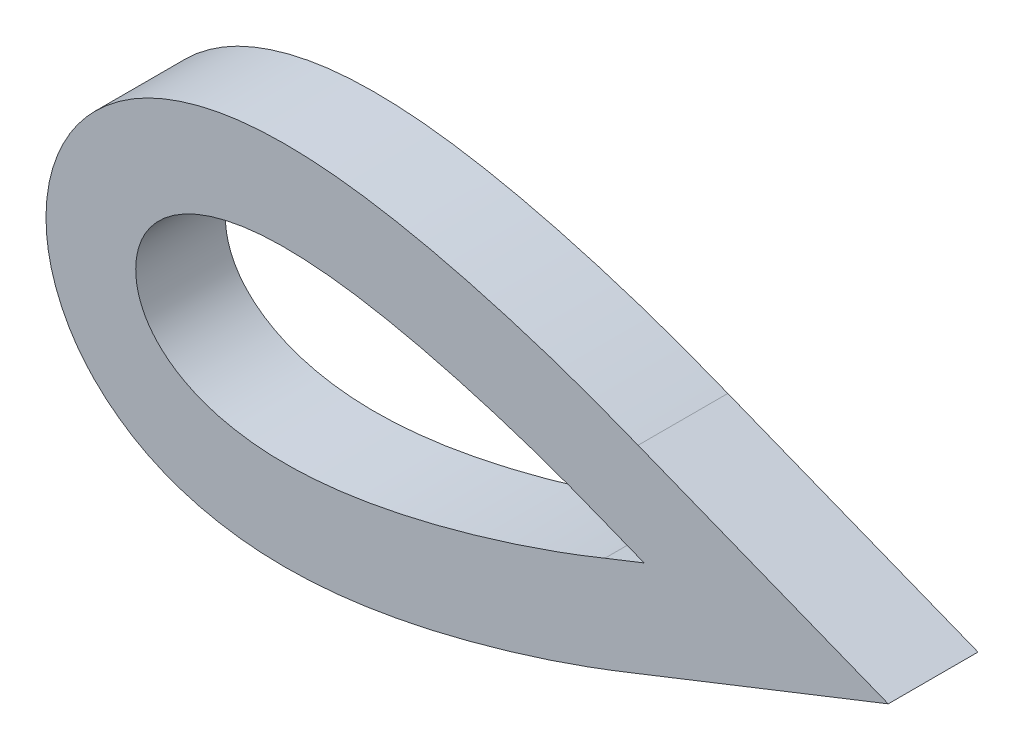
SolidWorks part; units mm, degrees
ref_plane "Front Plane" through (0, 0, 0) normal (0, 0, 1) x (1, 0, 0)
ref_plane "Top Plane" through (0, 0, 0) normal (0, 1, 0) x (1, 0, 0)
ref_plane "Right Plane" through (0, 0, 0) normal (1, 0, 0) x (0, 0, -1)
curve "Curve1"
  spline degree 3 poles (15, 0.0553, 0) (14.7504, 0.1555, 0) (14.2531, 0.3552, 0) (13.2557, 0.7272, 0) (12.0086, 1.1545, 0) (10.5081, 1.6108, 0) (9.0083, 2.0064, 0) (7.5085, 2.33, 0) (6.0074, 2.5603, 0) (4.7508, 2.6418, 0) (3.7477, 2.6098, 0) (2.9933, 2.5225, 0) (2.2339, 2.3534, 0) (1.6058, 2.116, 0) (1.1087, 1.8388, 0) (0.7182, 1.5477, 0) (0.3995, 1.204, 0) (0.0937, 0.6956, 0) (-0.0654, 0, 0) (0.0937, -0.6956, 0) (0.3995, -1.204, 0) (0.7182, -1.5477, 0) (1.1087, -1.8388, 0) (1.6058, -2.116, 0) (2.2339, -2.3534, 0) (2.9933, -2.5225, 0) (3.7477, -2.6098, 0) (4.7508, -2.6418, 0) (6.0074, -2.5603, 0) (7.5085, -2.33, 0) (9.0083, -2.0064, 0) (10.5081, -1.6108, 0) (12.0086, -1.1545, 0) (13.2557, -0.7272, 0) (14.2531, -0.3552, 0) (14.7504, -0.1555, 0) (15, -0.0553, 0) knots 0 0 0 0 0.024279 0.048376 0.096091 0.143261 0.189925 0.236074 0.281707 0.326919 0.349501 0.372229 0.39538 0.419578 0.432526 0.446653 0.463401 0.474441 0.5 0.525559 0.536599 0.553347 0.567474 0.580422 0.60462 0.627771 0.650499 0.673081 0.718293 0.763926 0.810075 0.856739 0.903909 0.951624 0.975721 1 1 1 1
sketch "Sketch2" plane through (0, 0, 0) normal (0, 0, 1) x (1, 0, 0)
  line L0 (-4.5404, 0) -> (25.6829, 0) construction
  line L1 (15.1863, -0.5193) -> (16.5, 0)
  line L2 (16.5, 0) -> (15.1863, 0.5193)
  line L3 (16.2965, -3.3063) -> (24.6607, 0)
  line L4 (24.6607, 0) -> (16.2965, 3.3063)
  spline S2 degree 1 poles (16.2965, 3.3063) (16.2965, -3.3063) knots 0 0 1 1 construction
  spline S3 degree 3 poles (-1320.7757, 4818.3054) (52.593, -66.6332) (43.0614, -10.0386) (13.8827, 1.0277) (13.5538, 1.1471) (12.5628, 1.4948) (11.897, 1.7114) (10.555, 2.113) (9.8788, 2.2983) (8.5131, 2.6287) (7.8237, 2.7742) (6.4262, 3.0035) (5.7175, 3.0874) (4.2802, 3.1439) (3.5498, 3.1187) (2.4551, 2.9201) (2.0895, 2.8263) (1.3734, 2.5578) (1.0227, 2.3846) (0.371, 1.9173) (0.0701, 1.622) (-0.2625, 1.0678) (-0.3513, 0.8634) (-0.4692, 0.441) (-0.5, 0.2215) (-0.5, -0.2215) (-0.4692, -0.441) (-0.3513, -0.8634) (-0.2625, -1.0678) (0.0701, -1.622) (0.371, -1.9173) (1.0227, -2.3846) (1.3734, -2.5578) (2.0895, -2.8263) (2.4551, -2.9201) (3.5498, -3.1187) (4.2802, -3.1439) (5.7175, -3.0874) (6.4262, -3.0035) (7.8237, -2.7742) (8.5131, -2.6287) (9.8788, -2.2983) (10.555, -2.113) (11.897, -1.7114) (12.5628, -1.4948) (13.5538, -1.1471) (13.8827, -1.0277) (43.0613, 10.0386) (52.5929, 66.6328) (-1320.7601, -4818.25) knots -2.715189 -2.715189 -2.715189 -2.715189 0.03125 0.03125 0.0625 0.0625 0.125 0.125 0.1875 0.1875 0.25 0.25 0.3125 0.3125 0.375 0.375 0.40625 0.40625 0.4375 0.4375 0.46875 0.46875 0.484375 0.484375 0.5 0.5 0.515625 0.515625 0.53125 0.53125 0.5625 0.5625 0.59375 0.59375 0.625 0.625 0.6875 0.6875 0.75 0.75 0.8125 0.8125 0.875 0.875 0.9375 0.9375 0.96875 0.96875 3.715178 3.715178 3.715178 3.715178 only from (15.1863, 0.5193) to (15.1863, -0.5193)
  spline S4 degree 3 poles (15.1863, 0.5193) (14.865, 0.6483) (14.5393, 0.7787) (13.8827, 1.0277) (13.5538, 1.1471) (12.5628, 1.4948) (11.897, 1.7114) (10.555, 2.113) (9.8788, 2.2983) (8.5131, 2.6287) (7.8237, 2.7742) (6.4262, 3.0035) (5.7175, 3.0874) (4.2802, 3.1439) (3.5498, 3.1187) (2.4551, 2.9201) (2.0895, 2.8263) (1.3734, 2.5578) (1.0227, 2.3846) (0.371, 1.9173) (0.0701, 1.622) (-0.2625, 1.0678) (-0.3513, 0.8634) (-0.4692, 0.441) (-0.5, 0.2215) (-0.5, -0.2215) (-0.4692, -0.441) (-0.3513, -0.8634) (-0.2625, -1.0678) (0.0701, -1.622) (0.371, -1.9173) (1.0227, -2.3846) (1.3734, -2.5578) (2.0895, -2.8263) (2.4551, -2.9201) (3.5498, -3.1187) (4.2802, -3.1439) (5.7175, -3.0874) (6.4262, -3.0035) (7.8237, -2.7742) (8.5131, -2.6287) (9.8788, -2.2983) (10.555, -2.113) (11.897, -1.7114) (12.5628, -1.4948) (13.5538, -1.1471) (13.8827, -1.0277) (14.5393, -0.7787) (14.865, -0.6483) (15.1863, -0.5193) knots 0 0 0 0 0.03125 0.03125 0.0625 0.0625 0.125 0.125 0.1875 0.1875 0.25 0.25 0.3125 0.3125 0.375 0.375 0.40625 0.40625 0.4375 0.4375 0.46875 0.46875 0.484375 0.484375 0.5 0.5 0.515625 0.515625 0.53125 0.53125 0.5625 0.5625 0.59375 0.59375 0.625 0.625 0.6875 0.6875 0.75 0.75 0.8125 0.8125 0.875 0.875 0.9375 0.9375 0.96875 0.96875 1 1 1 1
  spline S5 degree 3 poles (16.2965, 3.3063) (15.6063, 3.5834) (14.2174, 4.1141) (12.0872, 4.8037) (9.9129, 5.3999) (7.639, 5.8805) (5.5794, 6.1286) (3.7685, 6.1328) (2.3056, 5.9802) (0.6987, 5.5722) (-0.7545, 4.8724) (-1.9405, 3.8786) (-2.7598, 2.8545) (-3.3688, 1.4729) (-3.5656, 0) (-3.3688, -1.4729) (-2.7598, -2.8545) (-1.9405, -3.8786) (-0.7545, -4.8724) (0.6987, -5.5722) (2.3056, -5.9802) (3.7685, -6.1328) (5.5794, -6.1286) (7.639, -5.8805) (9.9129, -5.3999) (12.0872, -4.8037) (14.2174, -4.1141) (15.6063, -3.5834) (16.2965, -3.3063) knots 0.000239 0.000239 0.000239 0.000239 0.062709 0.125179 0.18765 0.25012 0.31259 0.343825 0.37506 0.406295 0.43753 0.453147 0.468765 0.484382 0.5 0.515618 0.531235 0.546853 0.56247 0.593705 0.62494 0.656175 0.68741 0.74988 0.81235 0.874821 0.937291 0.999761 0.999761 0.999761 0.999761
  dimension "D2" = 16.5
  dimension "D1" = 0.5
  dimension "D3" = 3
extrude "Boss-Extrude1" add sketch "Sketch2" along normal blind 3
